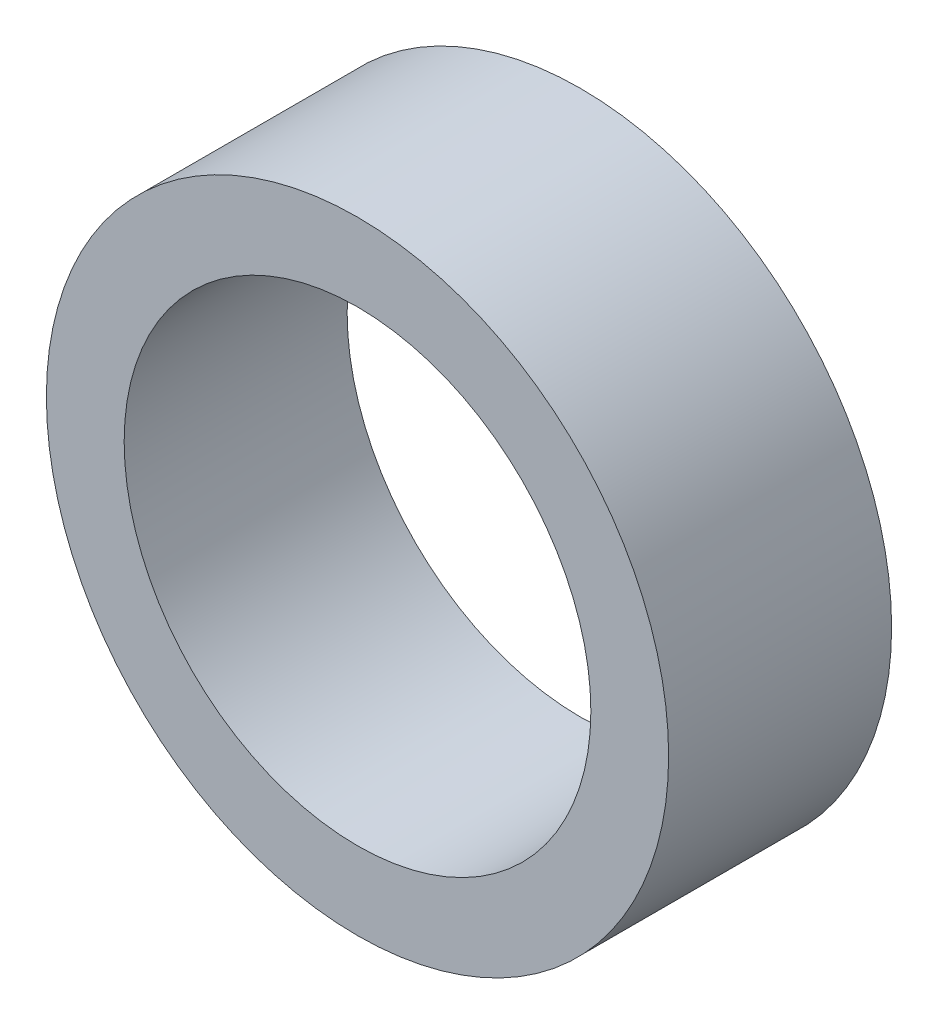
SolidWorks part; units mm, degrees
ref_plane "Plan de face" through (0, 0, 0) normal (0, 0, 1) x (1, 0, 0)
ref_plane "Plan de dessus" through (0, 0, 0) normal (0, 1, 0) x (1, 0, 0)
ref_plane "Plan de droite" through (0, 0, 0) normal (1, 0, 0) x (0, 0, -1)
sketch "Esquisse1" plane through (0, 0, 0) normal (0, 0, 1) x (1, 0, 0)
  circle A0 centre (0, 0) radius 2.25
  circle A1 centre (0, 0) radius 3
  dimension "D1" = 4.5
  dimension "D2" = 6
extrude "Boss.-Extru.1" add sketch "Esquisse1" along normal blind 2.15
